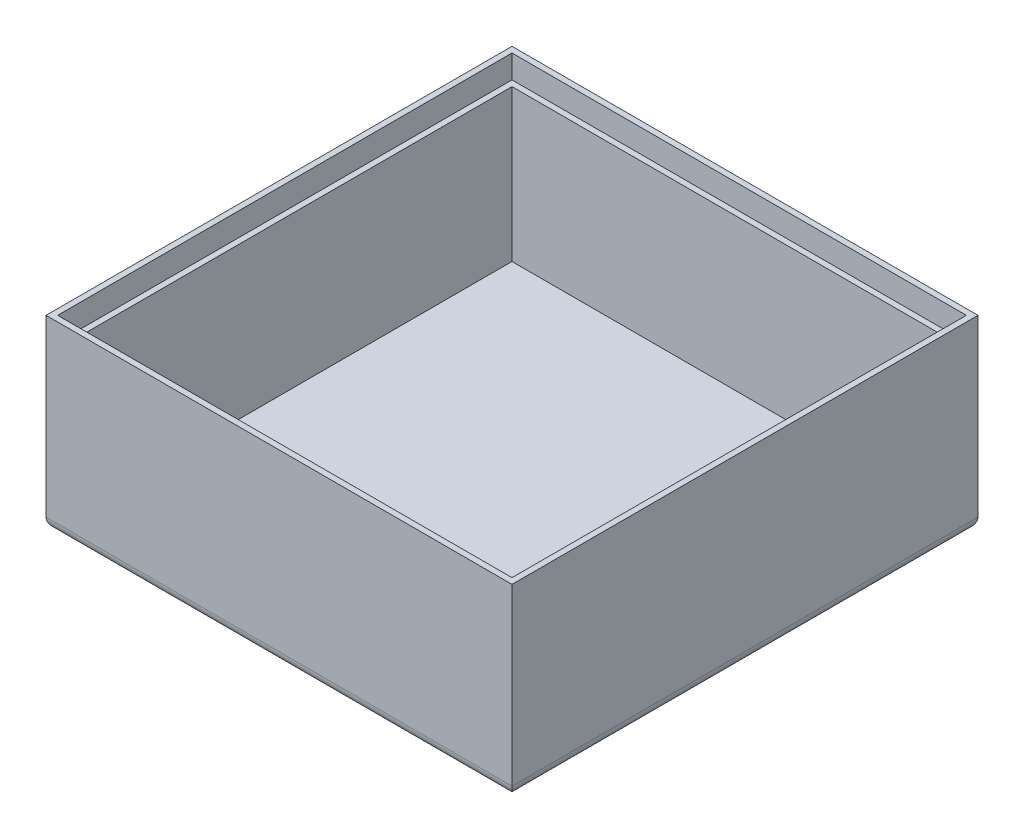
SolidWorks part; units mm, degrees
ref_plane "Front" through (0, 0, 0) normal (0, 0, 1) x (1, 0, 0)
ref_plane "Top" through (0, 0, 0) normal (0, 1, 0) x (1, 0, 0)
ref_plane "Right" through (0, 0, 0) normal (1, 0, 0) x (0, 0, -1)
sketch "Эскиз1" plane through (0, 0, 0) normal (0, 1, 0) x (1, 0, 0)
  line L1 (-1.085, 0.539) -> (38.915, 0.539)
  line L2 (-1.085, 0.539) -> (-1.085, -39.461)
  line L3 (-1.085, -39.461) -> (38.915, -39.461)
  line L4 (38.915, 0.539) -> (38.915, -39.461)
  dimension "D1" = 40
  dimension "D2" = 40
extrude "Бобышка-Вытянуть1" add sketch "Эскиз1" along normal blind 16
sketch "Эскиз2" plane through (0, 16, 0) normal (0, 1, 0) x (1, 0, 0)
  line L0 (-1.085, 0.539) -> (-1.085, -39.461) construction
  line L1 (-0.085, -0.461) -> (37.915, -0.461)
  line L2 (-0.085, -0.461) -> (-0.085, -38.461)
  line L3 (-0.085, -38.461) -> (37.915, -38.461)
  line L4 (37.915, -0.461) -> (37.915, -38.461)
  line L5 (38.915, 0.539) -> (-1.085, 0.539) construction
  dimension "D1" = 38
  dimension "D2" = 38
  dimension "D3" = 1
  dimension "D4" = 1
extrude "Вырез-Вытянуть2" cut sketch "Эскиз2" against normal blind 15
fillet "Скругление2" radius 1 4 edges at (38.915, 0, 19.461) (18.915, 0, 39.461) (-1.085, 0, 19.461) (18.915, 0, -0.539)
sketch "Эскиз5" plane through (0, 0, 38.461) normal (0, 0, -1) x (-1, 0, 0)
  line L0 (-37.915, 1) -> (-37.915, 16) construction
  line L1 (-37.915, 16) -> (0.085, 16)
  line L2 (-37.915, 16) -> (-37.915, 14)
  line L3 (-37.915, 14) -> (0.085, 14)
  line L4 (0.085, 16) -> (0.085, 14)
  line L5 (0.085, 1) -> (0.085, 16) construction
  line L6 (0.085, 16) -> (-37.915, 16) construction
  dimension "D1" = 2
  dimension "D2" = 0
extrude "Вырез-Вытянуть4" cut sketch "Эскиз5" against normal blind 0.5
sketch "Эскиз6" plane through (-0.085, 0, 0) normal (1, 0, 0) x (0, 0, -1)
  line L2 (-0.461, 16) -> (-38.961, 16)
  line L3 (-0.461, 16) -> (-0.461, 14)
  line L4 (-0.461, 14) -> (-38.961, 14)
  line L5 (-38.961, 16) -> (-38.961, 14)
  dimension "D1" = 0
  dimension "D2" = 2
extrude "Вырез-Вытянуть5" cut sketch "Эскиз6" against normal blind 0.5
sketch "Эскиз7" plane through (0, 0, 0.461) normal (0, 0, 1) x (1, 0, 0)
  line L0 (-0.585, 14) -> (-0.585, 16) construction
  line L1 (37.915, 16) -> (-0.585, 16)
  line L2 (37.915, 16) -> (37.915, 14)
  line L3 (37.915, 14) -> (-0.585, 14)
  line L4 (-0.585, 16) -> (-0.585, 14)
  dimension "D1" = 2
  dimension "D2" = 0
extrude "Вырез-Вытянуть6" cut sketch "Эскиз7" against normal blind 0.5
sketch "Эскиз8" plane through (37.915, 0, 0) normal (-1, 0, 0) x (0, 0, 1)
  line L0 (38.961, 16) -> (38.961, 14) construction
  line L1 (-0.039, 16) -> (38.961, 16)
  line L2 (-0.039, 16) -> (-0.039, 14)
  line L3 (-0.039, 14) -> (38.961, 14)
  line L4 (38.961, 16) -> (38.961, 14)
extrude "Вырез-Вытянуть7" cut sketch "Эскиз8" against normal blind 0.5
